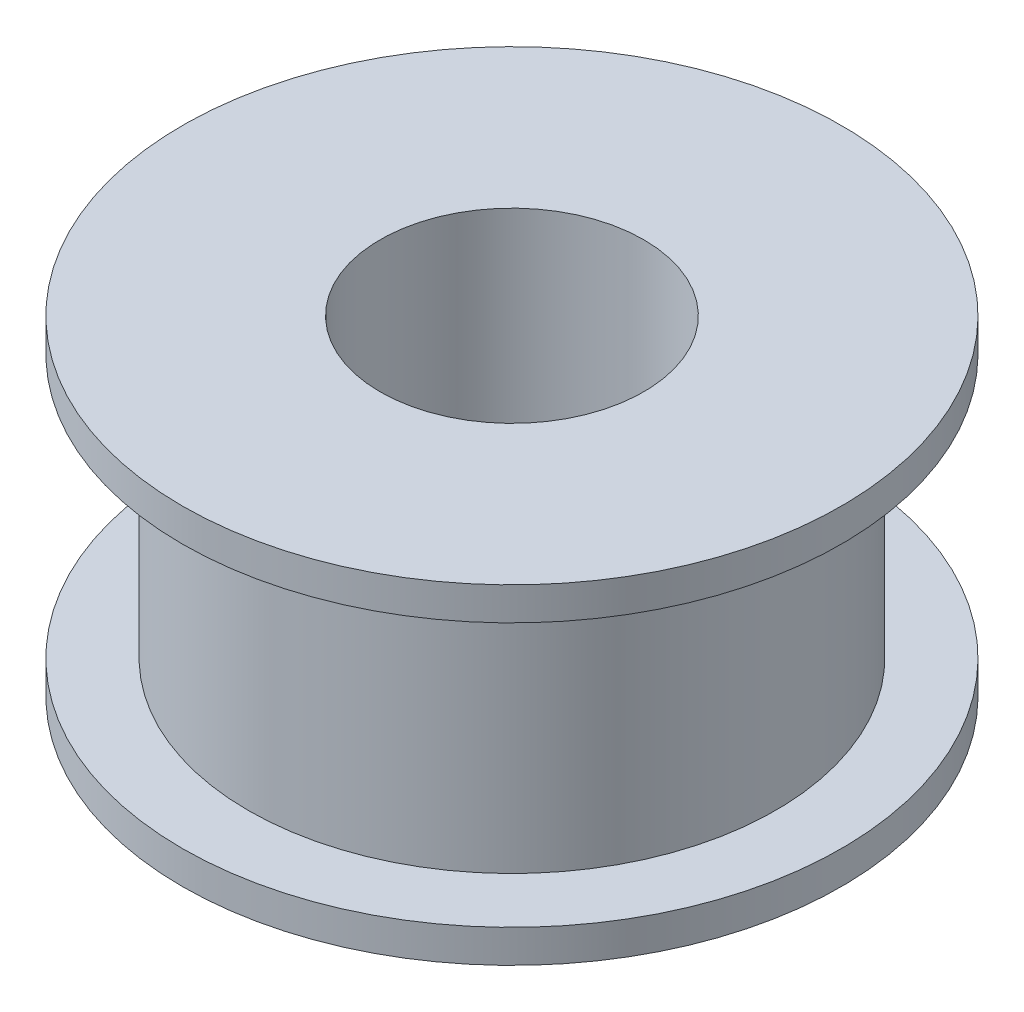
SolidWorks part; units mm, degrees
ref_plane "Front Plane" through (0, 0, 0) normal (0, 0, 1) x (1, 0, 0)
ref_plane "Top Plane" through (0, 0, 0) normal (0, 1, 0) x (1, 0, 0)
ref_plane "Right Plane" through (0, 0, 0) normal (1, 0, 0) x (0, 0, -1)
sketch "Sketch1" plane through (0, 0, 0) normal (0, 1, 0) x (1, 0, 0)
  circle A0 centre (0, 0) radius 25.4
  circle A1 centre (0, 0) radius 12.7
  dimension "D1" = 50.8
  dimension "D2" = 25.4
extrude "Boss-Extrude1" add sketch "Sketch1" along normal blind 25.4
ref_plane "Plane2" through (0, 12.7, 0) normal (0, 1, 0) x (1, 0, 0)
sketch "Sketch4" plane through (0, 25.4, 0) normal (0, 1, 0) x (1, 0, 0)
  circle A0 centre (0, 0) radius 31.75
  circle A1 centre (0, 0) radius 12.7
  dimension "D1" = 63.5
extrude "Boss-Extrude3" add sketch "Sketch4" along normal blind 3.175
mirror "Mirror2" about plane through (0, 12.7, 0) normal (0, 1, 0) of "Boss-Extrude3"
